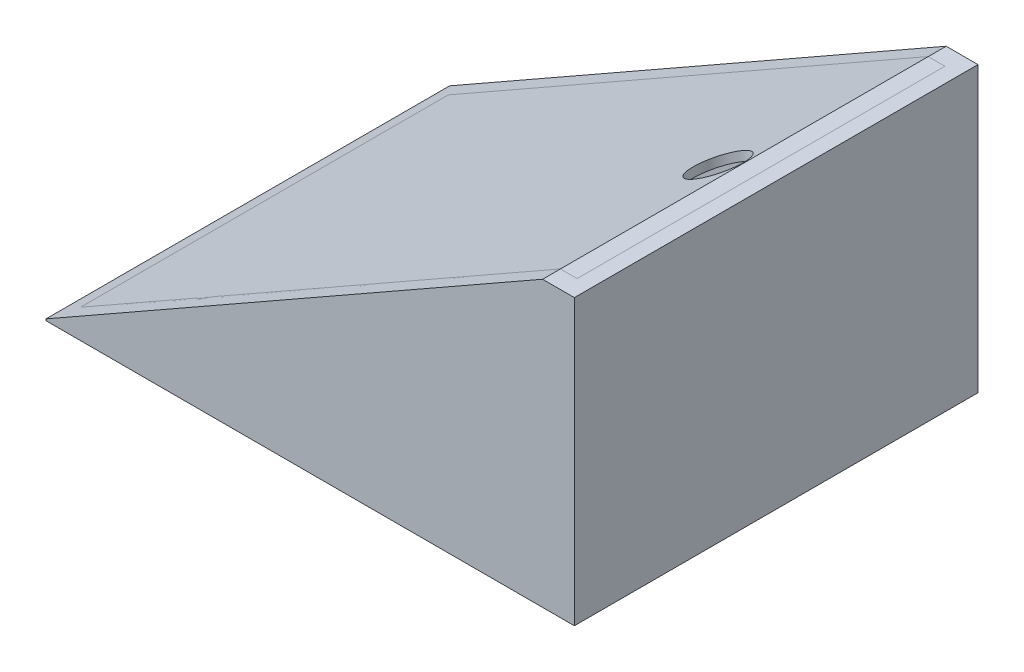
SolidWorks part; units mm, degrees
ref_plane "Front Plane" through (0, 0, 0) normal (0, 0, 1) x (1, 0, 0)
ref_plane "Top Plane" through (0, 0, 0) normal (0, 1, 0) x (1, 0, 0)
ref_plane "Right Plane" through (0, 0, 0) normal (1, 0, 0) x (0, 0, -1)
sketch "Sketch1" plane through (0, 0, 0) normal (0, 1, 0) x (1, 0, 0)
  line L1 (-46.0794, 14.7131) -> (69.1829, 14.7131)
  line L2 (-46.0794, 14.7131) -> (-46.0794, -73.3363)
  line L3 (-46.0794, -73.3363) -> (69.1829, -73.3363)
  line L4 (69.1829, 14.7131) -> (69.1829, -73.3363)
  line L5 (-42.4496, 10.7896) -> (65.8854, 10.7896)
  line L6 (-42.4496, 10.7896) -> (-42.4496, -69.4434)
  line L7 (-42.4496, -69.4434) -> (65.8854, -69.4434)
  line L8 (65.8854, 10.7896) -> (65.8854, -69.4434)
extrude "Boss-Extrude1" add sketch "Sketch1" along normal blind 62
sketch "Sketch2" plane through (0, 0, -10.7896) normal (0, 0, 1) x (1, 0, 0)
  line L0 (-42.4496, 0) -> (65.8854, 62)
  line L1 (-42.4496, 0) -> (-42.4496, 2.418)
  line L2 (-42.4496, 62) -> (-42.4496, 0) construction
  line L3 (-42.4496, 2.418) -> (62.2454, 62)
  line L4 (65.8854, 62) -> (-42.4496, 62) construction
  line L5 (62.2454, 62) -> (65.8854, 62)
extrude "Boss-Extrude5" add sketch "Sketch2" along normal blind 81 separate body
sketch "Sketch3" plane through (0, 0, -10.7896) normal (0, 0, 1) x (1, 0, 0)
  line L0 (62.2454, 62) -> (-47.989, -0.7345)
  line L1 (-47.989, -0.7345) -> (-64.5934, 83.1621)
  line L2 (-64.5934, 83.1621) -> (74.1787, 71.6452)
  line L3 (74.1787, 71.6452) -> (62.2454, 62)
extrude "Cut-Extrude1" cut sketch "Sketch3" along normal blind 140 and the other way blind 140
sketch "Sketch4" plane through (0, 0, 0) normal (0, 1, 0) x (1, 0, 0)
  circle A0 centre (56.5044, -29.3269) radius 5.4282
extrude "Cut-Extrude2" cut sketch "Sketch4" along normal blind 143
